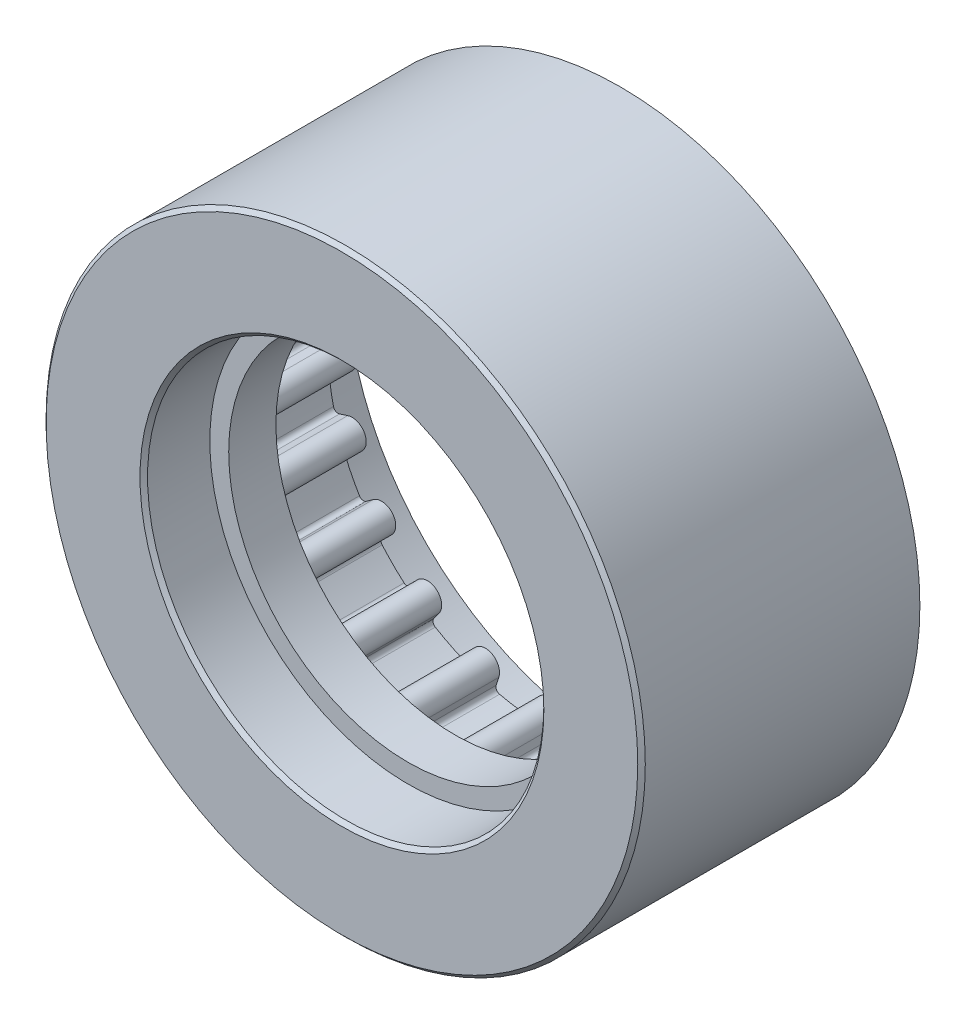
SolidWorks part; units mm, degrees
ref_plane "Ebene vorne" through (0, 0, 0) normal (0, 0, 1) x (1, 0, 0)
ref_plane "Ebene oben" through (0, 0, 0) normal (0, 1, 0) x (1, 0, 0)
ref_plane "Ebene rechts" through (0, 0, 0) normal (1, 0, 0) x (0, 0, -1)
ref_plane "Ebene1" through (0, 0, 0) normal (0, -1, 0) x (1, 0, 0)
sketch "Skizze1" plane through (0, 0, 0) normal (0, -1, 0) x (1, 0, 0)
  line L0 (31.75, 8.6) -> (0, 8.6)
  line L1 (0, 8.6) -> (0, -8.9)
  line L2 (0, -8.9) -> (31.75, -8.9)
  line L3 (31.75, -8.9) -> (31.75, 8.6)
  line L4 (0, 8.6) -> (0, -8.9) construction
  dimension "D1" = 31.75
  dimension "D2" = 17.5
revolve "Rotation1" add sketch "Skizze1" angle 360 about L4
sketch "Skizze2" plane through (0, 0, 8.6) normal (0, 0, 1) x (1, 0, 0)
  line L0 (-1.5, 22) -> (-1.5, 23.4521)
  line L1 (1.5, 22) -> (1.5, 23.4521)
  line L2 (5.3718, 21.3868) -> (5.8205, 22.7678)
  line L3 (8.225, 20.4597) -> (8.6737, 21.8407)
  line L4 (11.7178, 18.6801) -> (12.5713, 19.8548)
  line L5 (14.1448, 16.9167) -> (14.9983, 18.0915)
  line L6 (16.9167, 14.1448) -> (18.0915, 14.9983)
  line L7 (18.6801, 11.7178) -> (19.8548, 12.5713)
  line L8 (20.4597, 8.225) -> (21.8407, 8.6737)
  line L9 (21.3868, 5.3718) -> (22.7678, 5.8205)
  line L10 (22, 1.5) -> (23.4521, 1.5)
  line L11 (22, -1.5) -> (23.4521, -1.5)
  line L12 (21.3868, -5.3718) -> (22.7678, -5.8205)
  line L13 (20.4597, -8.225) -> (21.8407, -8.6737)
  line L14 (18.6801, -11.7178) -> (19.8548, -12.5713)
  line L15 (16.9167, -14.1448) -> (18.0915, -14.9983)
  line L16 (14.1448, -16.9167) -> (14.9983, -18.0915)
  line L17 (11.7178, -18.6801) -> (12.5713, -19.8548)
  line L18 (8.225, -20.4597) -> (8.6737, -21.8407)
  line L19 (5.3718, -21.3868) -> (5.8205, -22.7678)
  line L20 (1.5, -22) -> (1.5, -23.4521)
  line L21 (-1.5, -22) -> (-1.5, -23.4521)
  line L22 (-5.3718, -21.3868) -> (-5.8205, -22.7678)
  line L23 (-8.225, -20.4597) -> (-8.6737, -21.8407)
  line L24 (-11.7178, -18.6801) -> (-12.5713, -19.8548)
  line L25 (-14.1448, -16.9167) -> (-14.9983, -18.0915)
  line L26 (-16.9167, -14.1448) -> (-18.0915, -14.9983)
  line L27 (-18.6801, -11.7178) -> (-19.8548, -12.5713)
  line L28 (-20.4597, -8.225) -> (-21.8407, -8.6737)
  line L29 (-21.3868, -5.3718) -> (-22.7678, -5.8205)
  line L30 (-22, -1.5) -> (-23.4521, -1.5)
  line L31 (-22, 1.5) -> (-23.4521, 1.5)
  line L32 (-21.3868, 5.3718) -> (-22.7678, 5.8205)
  line L33 (-20.4597, 8.225) -> (-21.8407, 8.6737)
  line L34 (-18.6801, 11.7178) -> (-19.8548, 12.5713)
  line L35 (-16.9167, 14.1448) -> (-18.0915, 14.9983)
  line L36 (-14.1448, 16.9167) -> (-14.9983, 18.0915)
  line L37 (-11.7178, 18.6801) -> (-12.5713, 19.8548)
  line L38 (-8.225, 20.4597) -> (-8.6737, 21.8407)
  line L39 (-5.3718, 21.3868) -> (-5.8205, 22.7678)
  circle A0 centre (0, 22) radius 1.5
  circle A1 centre (0, 0) radius 23.5
  circle A2 centre (6.7984, 20.9232) radius 1.5
  circle A3 centre (12.9313, 17.7984) radius 1.5
  circle A4 centre (17.7984, 12.9313) radius 1.5
  circle A5 centre (20.9232, 6.7984) radius 1.5
  circle A6 centre (22, 0) radius 1.5
  circle A7 centre (20.9232, -6.7984) radius 1.5
  circle A8 centre (17.7984, -12.9313) radius 1.5
  circle A9 centre (12.9313, -17.7984) radius 1.5
  circle A10 centre (6.7984, -20.9232) radius 1.5
  circle A11 centre (0, -22) radius 1.5
  circle A12 centre (-6.7984, -20.9232) radius 1.5
  circle A13 centre (-12.9313, -17.7984) radius 1.5
  circle A14 centre (-17.7984, -12.9313) radius 1.5
  circle A15 centre (-20.9232, -6.7984) radius 1.5
  circle A16 centre (-22, 0) radius 1.5
  circle A17 centre (-20.9232, 6.7984) radius 1.5
  circle A18 centre (-17.7984, 12.9313) radius 1.5
  circle A19 centre (-12.9313, 17.7984) radius 1.5
  circle A20 centre (-6.7984, 20.9232) radius 1.5
  dimension "D1" = 3
  dimension "D3" = 20
  dimension "D2" = 22
extrude "Schnitt-Linear austragen1" cut sketch "Skizze2" against normal through all contours A20 L38 A1 L37 A19 L36 L35 A18 L34 L33 A17 L32 L31 A16 L30 L29 A15 L28 L27 A14 L26 L25 A13 L24 L23 A12 L22 L21 A11 L20 L19 A10 L18 L17 A9 L16 L15 A8 L14
sketch "Skizze3" plane through (0, 0, 0) normal (0, 1, 0) x (1, 0, 0)
  line L0 (29, 8.9) -> (0, 8.9)
  line L1 (0, 8.9) -> (0, 1.4)
  line L2 (0, 1.4) -> (26.5, 1.4)
  line L3 (26.5, 1.4) -> (27, 1.9)
  line L4 (27, 1.9) -> (29, 1.9)
  line L5 (29, 1.9) -> (29, 8.9)
  line L6 (0, 8.9) -> (0, 1.4) construction
  line L7 (31.75, 8.9) -> (-31.75, 8.9) construction
  dimension "D1" = 7
  dimension "D2" = 0.5
  dimension "D3" = 45
  dimension "D4" = 2
  dimension "D5" = 29
revolve "Schnitt-Rotation1" cut sketch "Skizze3" angle 360 about L6
sketch "Skizze13" plane through (0, 0, 8.6) normal (0, 0, 1) x (1, 0, 0)
  circle A1 centre (0, 0) radius 31.75
  circle A162 centre (0, 0) radius 21
  dimension "D1" = 42
extrude "Aufsatz-Linear austragen1" add sketch "Skizze13" along normal blind 12
sketch "Skizze14" plane through (0, 0, 8.6) normal (0, 0, -1) x (-1, 0, 0)
  circle A0 centre (0, 0) radius 19
  circle A1 centre (0, 0) radius 21
  dimension "D1" = 38
extrude "Aufsatz-Linear austragen2" add sketch "Skizze14" against normal offset from surface (5 mm away) 7
fillet "Verrundung1" radius 0.5 40 edges at (-23.4521, 1.5, 3.6) (-21.8407, 8.6737, 3.6) (-22.7678, 5.8205, 3.6) (-19.8548, 12.5713, 3.6) (-23.4521, -1.5, 3.6) (-21.8407, -8.6737, 3.6) (-18.0915, -14.9983, 3.6) (-22.7678, -5.8205, 3.6) (-19.8548, -12.5713, 3.6) (-14.9983, -18.0915, 3.6) (-8.6737, -21.8407, 3.6) (-1.5, -23.4521, 3.6) (-12.5713, -19.8548, 3.6) (1.5, -23.4521, 3.6) (-5.8205, -22.7678, 3.6) (5.8205, -22.7678, 3.6) (12.5713, -19.8548, 3.6) (8.6737, -21.8407, 3.6) (14.9983, -18.0915, 3.6) (18.0915, -14.9983, 3.6) (21.8407, -8.6737, 3.6) (19.8548, -12.5713, 3.6) (22.7678, -5.8205, 3.6) (23.4521, -1.5, 3.6) (23.4521, 1.5, 3.6) (22.7678, 5.8205, 3.6) (19.8548, 12.5713, 3.6) (21.8407, 8.6737, 3.6) (18.0915, 14.9983, 3.6) (14.9983, 18.0915, 3.6) (8.6737, 21.8407, 3.6) (12.5713, 19.8548, 3.6) (5.8205, 22.7678, 3.6) (1.5, 23.4521, 3.6) (-5.8205, 22.7678, 3.6) (-1.5, 23.4521, 3.6) (-8.6737, 21.8407, 3.6) (-12.5713, 19.8548, 3.6) (-14.9983, 18.0915, 3.6) (-18.0915, 14.9983, 3.6)
chamfer "Fase5" distance 0.4 angle 45 2 edges at (21, 0, 20.6) (31.75, 0, 20.6)
